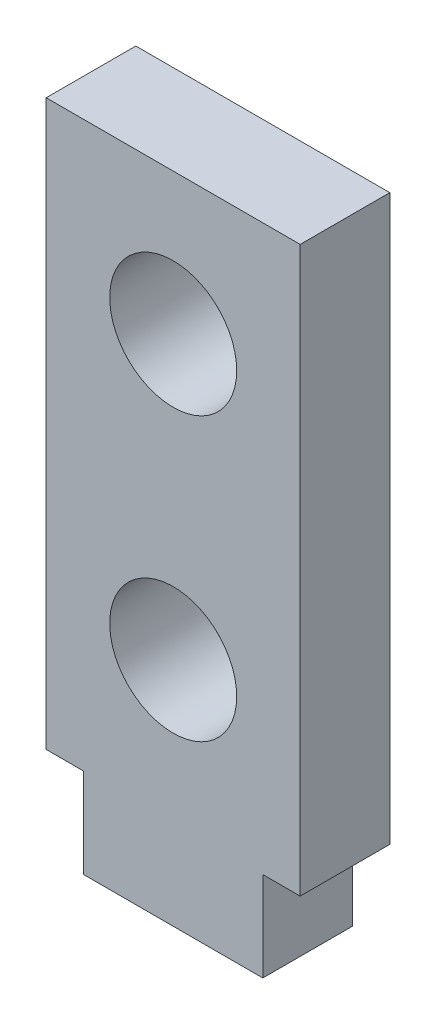
SolidWorks part; units mm, degrees
material "Acrylic (Medium-high impact)"
ref_plane "Front Plane" through (0, 0, 0) normal (0, 0, 1) x (1, 0, 0)
ref_plane "Top Plane" through (0, 0, 0) normal (0, 1, 0) x (1, 0, 0)
ref_plane "Right Plane" through (0, 0, 0) normal (1, 0, 0) x (0, 0, -1)
sketch "Sketch1" plane through (0, 0, 0) normal (0, 0, 1) x (1, 0, 0)
  line L0 (4.5, -3.175) -> (4.5, 20) construction
  line L1 (0, 0) -> (1.325, 0)
  line L2 (0, 0) -> (0, 20)
  line L3 (0, 20) -> (9, 20)
  line L4 (9, 0) -> (9, 20)
  line L5 (1.325, 0) -> (1.325, -3.175)
  line L6 (1.325, -3.175) -> (7.675, -3.175)
  line L7 (7.675, -3.175) -> (7.675, 0)
  line L8 (7.675, 0) -> (9, 0)
  circle A0 centre (4.5, 5) radius 2.25
  circle A1 centre (4.5, 15) radius 2.25
  dimension "D1" = 5
  dimension "D3" = 4.5
  dimension "D2" = 10
  dimension "D4" = 5
  dimension "D5" = 9
  dimension "D6" = 6.35
  dimension "D7" = 3.175
  dimension "D8" = 3.175
  dimension "D9" = 1.325
extrude "Boss-Extrude2" add sketch "Sketch1" along normal blind 3.175
